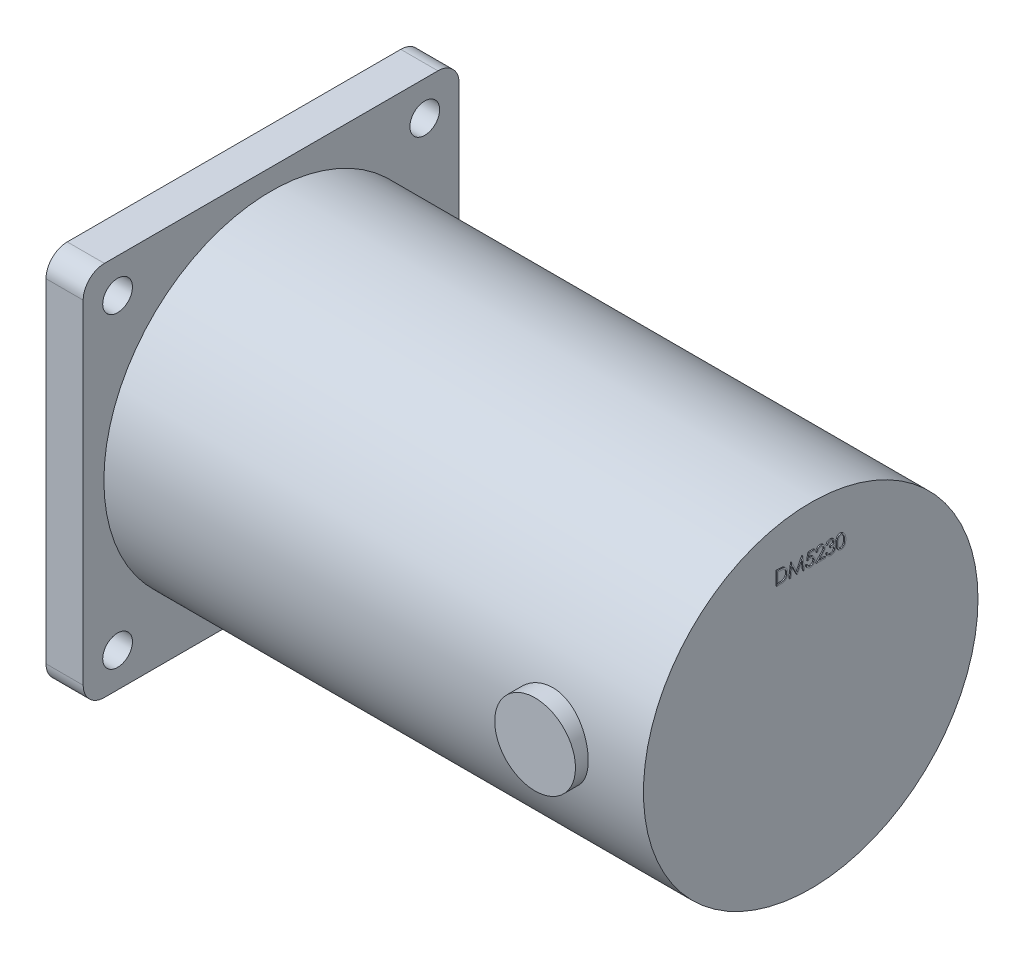
SolidWorks part; units mm, degrees
ref_plane "Front Plane" through (0, 0, 0) normal (0, 0, 1) x (1, 0, 0)
ref_plane "Top Plane" through (0, 0, 0) normal (0, 1, 0) x (1, 0, 0)
ref_plane "Right Plane" through (0, 0, 0) normal (1, 0, 0) x (0, 0, -1)
sketch "Sketch1" plane through (0, 0, 0) normal (1, 0, 0) x (0, 0, -1)
  circle A0 centre (0, 0) radius 40.005
  dimension "D1" = 80.01
extrude "Boss-Extrude1" add sketch "Sketch1" against normal blind 129.032
sketch "Sketch2" plane through (-129.032, 0, 0) normal (-1, 0, 0) x (0, 0, 1)
  line L1 (-44.958, 44.958) -> (44.958, 44.958)
  line L2 (-44.958, 44.958) -> (-44.958, -44.958)
  line L3 (-44.958, -44.958) -> (44.958, -44.958)
  line L4 (44.958, 44.958) -> (44.958, -44.958)
  line L5 (-44.958, 44.958) -> (44.958, -44.958) construction
  line L6 (-44.958, -44.958) -> (44.958, 44.958) construction
  point P0 (0, 0)
  dimension "D1" = 89.916
  dimension "D2" = 89.916
extrude "Boss-Extrude2" add sketch "Sketch2" along normal blind 8.89
fillet "Fillet1" radius 5.08 4 edges at (-133.477, 44.958, -44.958) (-133.477, -44.958, -44.958) (-133.477, -44.958, 44.958) (-133.477, 44.958, 44.958)
sketch "Sketch3" plane through (-137.922, 0, 0) normal (-1, 0, 0) x (0, 0, 1)
  circle A0 centre (0, 0) radius 41.529
  dimension "D1" = 83.058
extrude "Boss-Extrude3" add sketch "Sketch3" along normal blind 2
sketch "Sketch4" plane through (-137.922, 0, 0) normal (-1, 0, 0) x (0, 0, 1)
  line L0 (0, 0) -> (36.7292, 36.7292) construction
  line L1 (-44.958, 0) -> (44.958, 0) construction
  line L2 (-44.958, 39.878) -> (-44.958, -39.878) construction
  line L3 (44.958, -39.878) -> (44.958, 39.878) construction
  circle A0 centre (36.7292, 36.7292) radius 3.556
  dimension "D3" = 7.112
  dimension "D1" = 45
  dimension "D2" = 51.943
extrude "Cut-Extrude4" cut sketch "Sketch4" against normal up to next
pattern_circular "CirPattern1" count 4 over 360 about axis through (0, 0, 0) along (1, 0, 0) of "Cut-Extrude4"
sketch "Sketch6" plane through (-139.922, 0, 0) normal (-1, 0, 0) x (0, 0, 1)
  circle A0 centre (0, 0) radius 5
  dimension "D1" = 10
extrude "Boss-Extrude4" add sketch "Sketch6" along normal blind 29.5
ref_plane "Plane1" through (0, 2.6604, 0) normal (0, 1, 0) x (1, 0, 0)
sketch "Sketch7" plane through (0, 2.6604, 0) normal (0, 1, 0) x (1, 0, 0)
  line L0 (-169.422, 0) -> (-137.6619, 0) construction
  line L1 (-169.422, 5) -> (-169.422, -5) construction
  line L2 (-169.422, 2.0312) -> (-128.0127, 2.0312)
  line L3 (-169.422, -1.9688) -> (-147.324, -1.9688)
  line L4 (-169.422, 2.0312) -> (-169.422, -1.9688)
  arc A1 (-147.324, -1.9688) -> (-128.0127, 2.0312) centre (-137.6619, 0) ccw
  point P5 (-139.11, 0)
  dimension "D1" = 4
  dimension "D2" = 22.098
extrude "Boss-Extrude5" add sketch "Sketch7" along normal blind 4
ref_plane "Plane2" through (0, 0, 40.005) normal (0, 0, 1) x (1, 0, 0)
sketch "Sketch8" plane through (0, 0, 40.005) normal (0, 0, 1) x (1, 0, 0)
  line L0 (0, 0) -> (-22.86, 0) construction
  circle A0 centre (-22.86, 0) radius 9.652
  dimension "D2" = 19.304
  dimension "D1" = 22.86
extrude "Boss-Extrude6" add sketch "Sketch8" along normal blind 3.048 and the other way up to surface (3.048 mm away)
mirror "Mirror1" about plane through (0, 0, 0) normal (0, 0, 1) of "Boss-Extrude6"
sketch "Sketch10" plane through (0, 0, 0) normal (1, 0, 0) x (0, 0, -1)
  text T0 "DM5230"
extrude "Boss-Extrude7" add sketch "Sketch10" along normal blind 0.254
